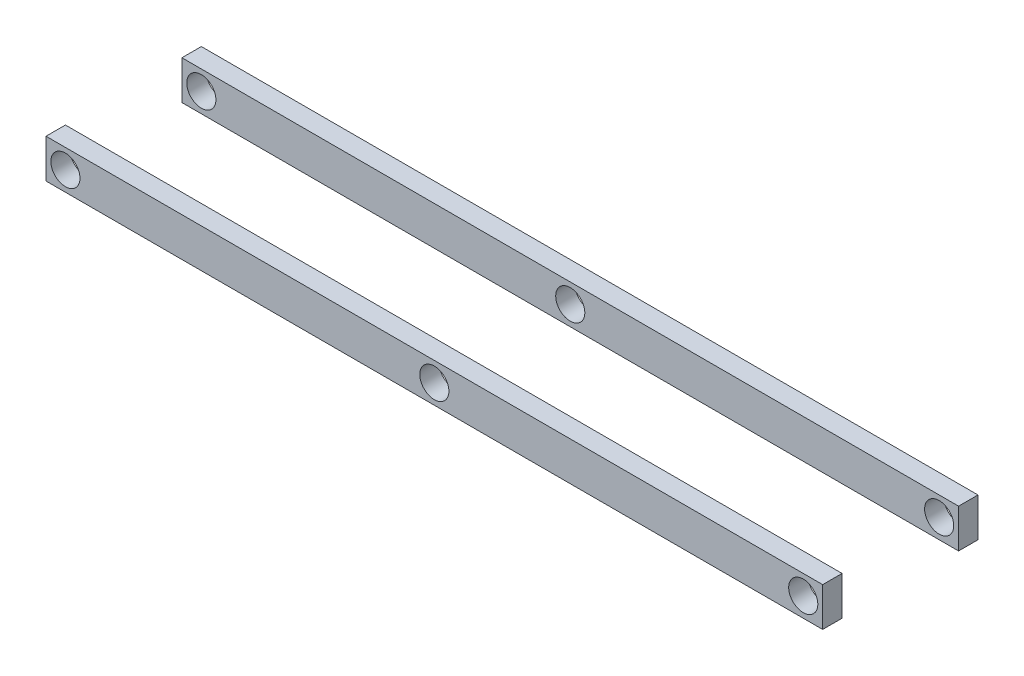
SolidWorks part; units mm, degrees
ref_plane "Front Plane" through (0, 0, 0) normal (0, 0, 1) x (1, 0, 0)
ref_plane "Top Plane" through (0, 0, 0) normal (0, 1, 0) x (1, 0, 0)
ref_plane "Right Plane" through (0, 0, 0) normal (1, 0, 0) x (0, 0, -1)
sketch "Sketch1" plane through (0, 0, 0) normal (0, 1, 0) x (1, 0, 0)
  line L1 (0, 0) -> (40, 0)
  line L2 (0, 0) -> (0, 8)
  line L3 (0, 8) -> (40, 8)
  line L4 (40, 0) -> (40, 8)
  dimension "D1" = 8
  dimension "D2" = 40
extrude "Boss-Extrude1" add sketch "Sketch1" along normal blind 2
sketch "Sketch2" plane through (0, 2, 0) normal (0, 1, 0) x (1, 0, 0)
  line L1 (0, 8) -> (0, 0) construction
  line L2 (0, 7) -> (40, 7)
  line L3 (40, 0) -> (40, 8) construction
  line L4 (40, 7) -> (40, 1)
  line L5 (40, 1) -> (0, 1)
  line L6 (0, 1) -> (0, 7)
  dimension "D2" = 6
extrude "Cut-Extrude1" cut sketch "Sketch2" against normal blind 2
sketch "Sketch3" plane through (0, 0, 0) normal (0, 0, 1) x (1, 0, 0)
  circle A0 centre (20, 1) radius 0.75
  circle A1 centre (1, 1) radius 0.75
  circle A2 centre (39, 1) radius 0.75
  dimension "D1" = 1.5
  dimension "D3" = 1.5
  dimension "D4" = 1.5
extrude "Cut-Extrude2" cut sketch "Sketch3" against normal through all
